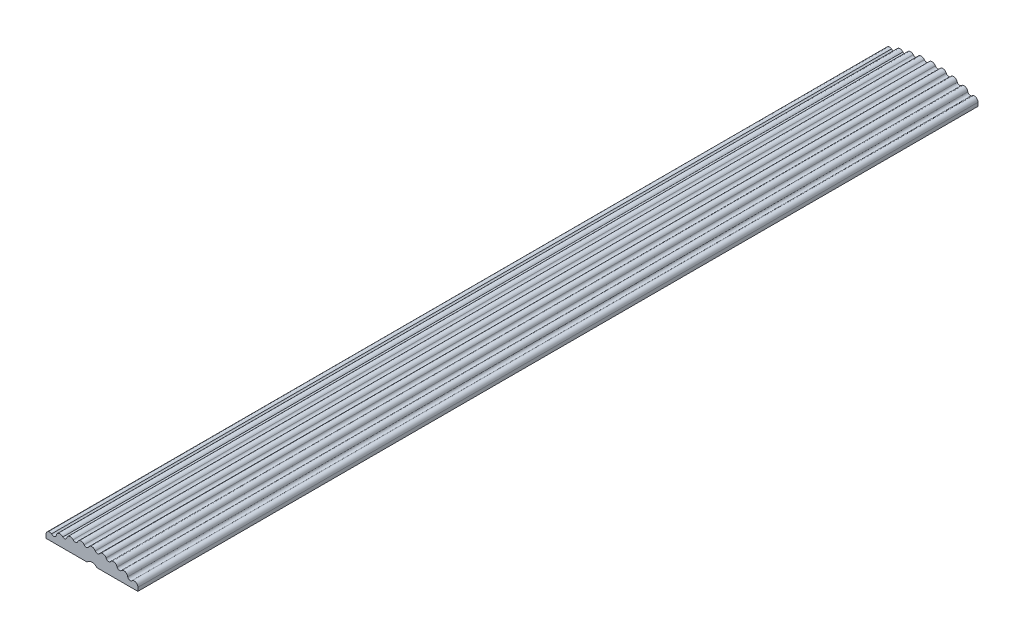
SolidWorks part; units mm, degrees
ref_plane "Front Plane" through (0, 0, 0) normal (0, 0, 1) x (1, 0, 0)
ref_plane "Top Plane" through (0, 0, 0) normal (0, 1, 0) x (1, 0, 0)
ref_plane "Right Plane" through (0, 0, 0) normal (1, 0, 0) x (0, 0, -1)
ref_plane "Plane1" through (0, 0, 152.4) normal (0, 0, 1) x (1, 0, 0)
sketch "Sketch1" plane through (0, 0, 152.4) normal (0, 0, 1) x (1, 0, 0)
  line L0 (-1.5875, 3.4728) -> (-1.5875, 5.2762)
  line L1 (1.5875, 5.2762) -> (1.5875, 3.4728)
  line L2 (-11.1125, 7.1558) -> (-11.1125, 6.2992)
  line L3 (-11.1125, 6.2992) -> (-4.0132, 6.2992)
  line L4 (-3.5052, 5.7912) -> (-3.5052, 3.9808)
  line L5 (-4.0132, 3.4728) -> (-4.7625, 3.4728)
  line L6 (-4.7625, 3.4728) -> (-2.5635, 1.1147)
  line L7 (2.5635, 1.1147) -> (4.7625, 3.4728)
  line L8 (4.7625, 3.4728) -> (4.0132, 3.4728)
  line L9 (3.5052, 3.9808) -> (3.5052, 5.7912)
  line L10 (4.0132, 6.2992) -> (11.1125, 6.2992)
  line L11 (11.1125, 6.2992) -> (11.1125, 7.1558)
  arc A0 (-1.5875, 5.2762) -> (1.5875, 5.2762) centre (0, 5.2762) cw
  arc A1 (1.5875, 3.4728) -> (-1.5875, 3.4728) centre (0, 3.4728) cw
  arc A2 (-9.7701, 7.9205) -> (-11.1125, 7.1558) centre (-10.2235, 7.1558) ccw
  arc A3 (-4.0132, 6.2992) -> (-3.5052, 5.7912) centre (-4.0132, 5.7912) cw
  arc A4 (-3.5052, 3.9808) -> (-4.0132, 3.4728) centre (-4.0132, 3.9808) cw
  arc A5 (-2.5635, 1.1147) -> (2.5635, 1.1147) centre (0, 3.5052) ccw
  arc A6 (4.0132, 3.4728) -> (3.5052, 3.9808) centre (4.0132, 3.9808) cw
  arc A7 (3.5052, 5.7912) -> (4.0132, 6.2992) centre (4.0132, 5.7912) cw
  arc A8 (11.1125, 7.1558) -> (9.7701, 7.9205) centre (10.2235, 7.1558) ccw
  arc A9 (9.7701, 7.9205) -> (8.6424, 8.104) centre (9.2508, 8.2858) cw
  arc A10 (8.6424, 8.104) -> (7.0531, 8.5989) centre (7.7548, 8.0531) ccw
  arc A11 (7.0531, 8.5989) -> (6.0854, 8.8633) centre (6.6719, 9.1067) cw
  arc A12 (6.0854, 8.8633) -> (4.5521, 9.2956) centre (5.2116, 8.6996) ccw
  arc A13 (4.5521, 9.2956) -> (3.4212, 9.4716) centre (4.029, 9.6556) cw
  arc A14 (3.4212, 9.4716) -> (1.877, 9.5805) centre (2.6183, 9.0899) ccw
  arc A15 (1.877, 9.5805) -> (0.7964, 9.6152) centre (1.3474, 9.9309) cw
  arc A16 (0.7964, 9.6152) -> (-0.7964, 9.6152) centre (0, 9.2202) ccw
  arc A17 (-0.7964, 9.6152) -> (-1.877, 9.5805) centre (-1.3474, 9.9309) cw
  arc A18 (-1.877, 9.5805) -> (-3.4212, 9.4716) centre (-2.6183, 9.0899) ccw
  arc A19 (-3.4212, 9.4716) -> (-4.5521, 9.2956) centre (-4.029, 9.6556) cw
  arc A20 (-4.5521, 9.2956) -> (-6.0854, 8.8633) centre (-5.2116, 8.6996) ccw
  arc A21 (-6.0854, 8.8633) -> (-7.0531, 8.5989) centre (-6.6719, 9.1067) cw
  arc A22 (-7.0531, 8.5989) -> (-8.6424, 8.104) centre (-7.7548, 8.0531) ccw
  arc A23 (-8.6424, 8.104) -> (-9.7701, 7.9205) centre (-9.2508, 8.2858) cw
extrude "Boss-Extrude2" add sketch "Sketch1" along normal blind 203.2
sketch "Sketch2" plane through (0, 0, 0) normal (0, 1, 0) x (1, 0, 0)
  line L0 (11.1125, -355.6) -> (11.1125, -152.4) construction
  line L1 (-11.1125, -152.4) -> (11.1125, -152.4)
  line L2 (-11.1125, -152.4) -> (-11.1125, -177.8)
  line L3 (-11.1125, -177.8) -> (11.1125, -177.8)
  line L4 (11.1125, -152.4) -> (11.1125, -177.8)
  line L5 (-11.1125, -355.6) -> (-11.1125, -152.4) construction
  line L6 (11.1125, -355.6) -> (-11.1125, -355.6)
  line L7 (11.1125, -355.6) -> (11.1125, -330.2)
  line L8 (11.1125, -330.2) -> (-11.1125, -330.2)
  line L9 (-11.1125, -355.6) -> (-11.1125, -330.2)
  dimension "D1" = 25.4
  dimension "D2" = 25.4
extrude "Cut-Extrude1" cut sketch "Sketch2" along normal up to surface (6.2992 mm away) up to face at (7.5629, 6.2992, 254)
